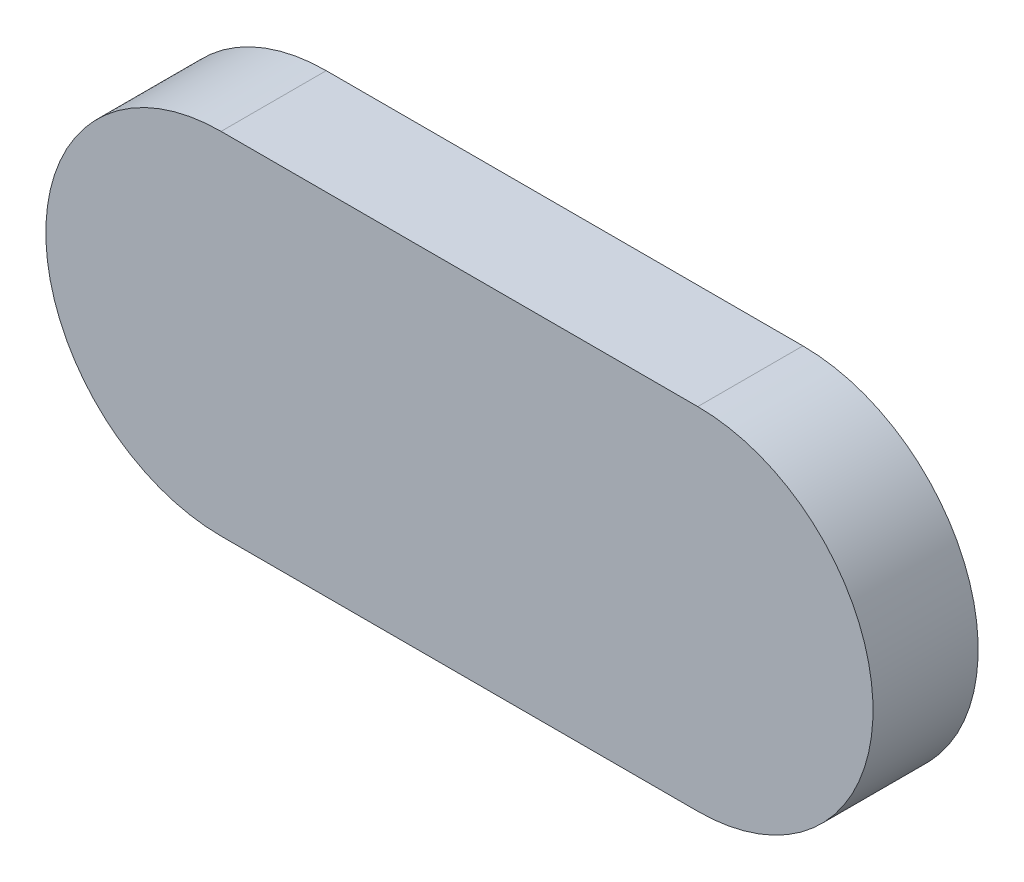
SolidWorks part; units mm, degrees
ref_plane "Front Plane" through (0, 0, 0) normal (0, 0, 1) x (1, 0, 0)
ref_plane "Top Plane" through (0, 0, 0) normal (0, 1, 0) x (1, 0, 0)
ref_plane "Right Plane" through (0, 0, 0) normal (1, 0, 0) x (0, 0, -1)
sketch "Sketch1" plane through (0, 0, 0) normal (0, 0, 1) x (1, 0, 0)
  line L1 (-34, 25) -> (34, 25)
  line L2 (-34, 25) -> (-34, -25)
  line L3 (-34, -25) -> (34, -25)
  line L4 (34, 25) -> (34, -25)
  line L5 (-34, 25) -> (34, -25) construction
  line L6 (-34, -25) -> (34, 25) construction
  arc A0 (34, 25) -> (34, -25) centre (34, 0) cw
  arc A1 (-34, -25) -> (-34, 25) centre (-34, 0) cw
  circle A2 centre (34, 0) radius 15 construction
  circle A3 centre (-34, 0) radius 15 construction
  point P0 (0, 0)
  dimension "D3" = 30
  dimension "D1" = 50
  dimension "D2" = 68
extrude "Boss-Extrude1" add sketch "Sketch1" along normal blind 15 contours L4 L1 L2 L3 | A1 L2 | A0 L4
sketch "Sketch3" plane through (0, 0, 15) normal (0, 0, 1) x (1, 0, 0)
  line L4 (-34, -25) -> (34, -25)
  line L5 (34, 25) -> (-34, 25)
  line L6 (-34, -25) -> (34, -25) construction
  line L7 (34, 25) -> (-34, 25) construction
  arc A4 (34, -25) -> (34, 25) centre (34, 0) ccw
  arc A5 (-34, 25) -> (-34, -25) centre (-34, 0) ccw
  arc A6 (34, -25) -> (34, 25) centre (34, 0) ccw construction
  arc A7 (-34, 25) -> (-34, -25) centre (-34, 0) ccw construction
  dimension "D1" = 0
